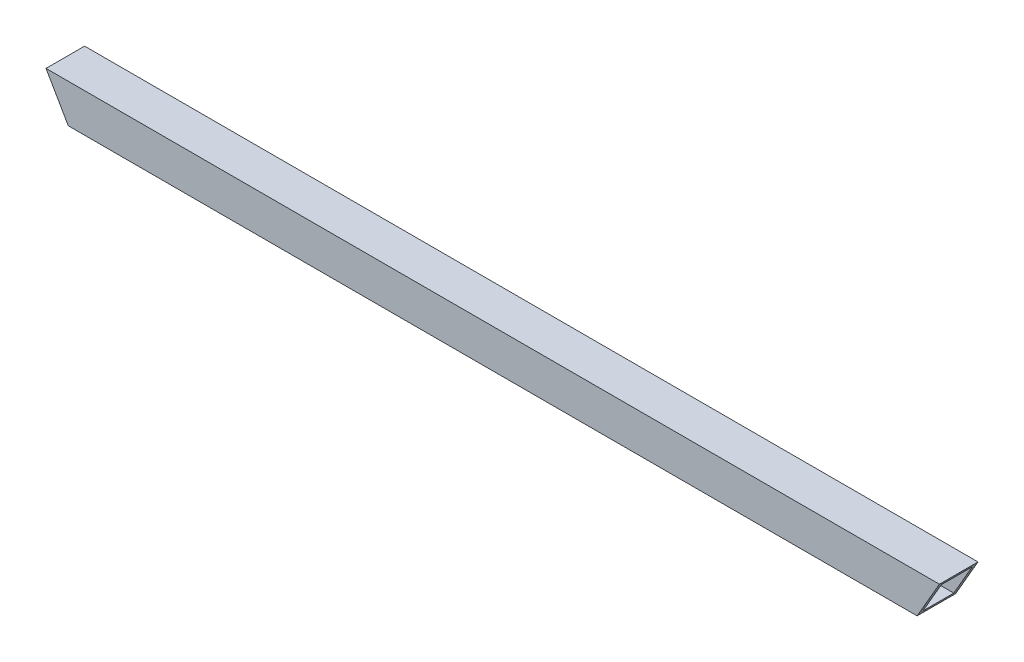
SolidWorks part; units mm, degrees
material "Ti-6Al-4VSolution treated and aged (SS)"
ref_plane "Front Plane" through (0, 0, 0) normal (0, 0, 1) x (1, 0, 0)
ref_plane "Top Plane" through (0, 0, 0) normal (0, 1, 0) x (1, 0, 0)
ref_plane "Right Plane" through (0, 0, 0) normal (1, 0, 0) x (0, 0, -1)
sketch "Sketch3" plane through (0, 0, 0) normal (0, 0, 1) x (1, 0, 0)
  line L0 (0, 0) -> (-1157.735, 0)
  line L1 (-1157.735, 0) -> (-1128.8675, -50)
  line L2 (-1128.8675, -50) -> (-28.8675, -50)
  line L3 (-28.8675, -50) -> (0, 0)
  dimension "D1" = 50
  dimension "D2" = 1100
  dimension "D3" = 60
  dimension "D4" = 60
extrude "Boss-Extrude1" add sketch "Sketch3" along normal blind 50 contours L0 L1 L2 L3
sketch "Sketch4" plane through (0, 0, 0) normal (0.866, -0.5, 0) x (0, 0, -1)
  line L0 (-45, -5) -> (-5, -5)
  line L1 (-5, -5) -> (-5, -52.735)
  line L2 (-5, -52.735) -> (-45, -52.735)
  line L3 (-45, -52.735) -> (-45, -5)
  line L4 (0, -57.735) -> (0, 0) construction
  line L5 (-50, 0) -> (0, 0) construction
  line L6 (-50, -57.735) -> (-50, 0) construction
  line L7 (-50, -57.735) -> (0, -57.735) construction
  dimension "D1" = 5
  dimension "D2" = 5
  dimension "D3" = 5
  dimension "D4" = 5
extrude "Cut-Extrude1" cut sketch "Sketch4" along direction (-1, 0, 0) on the side against the normal through all
